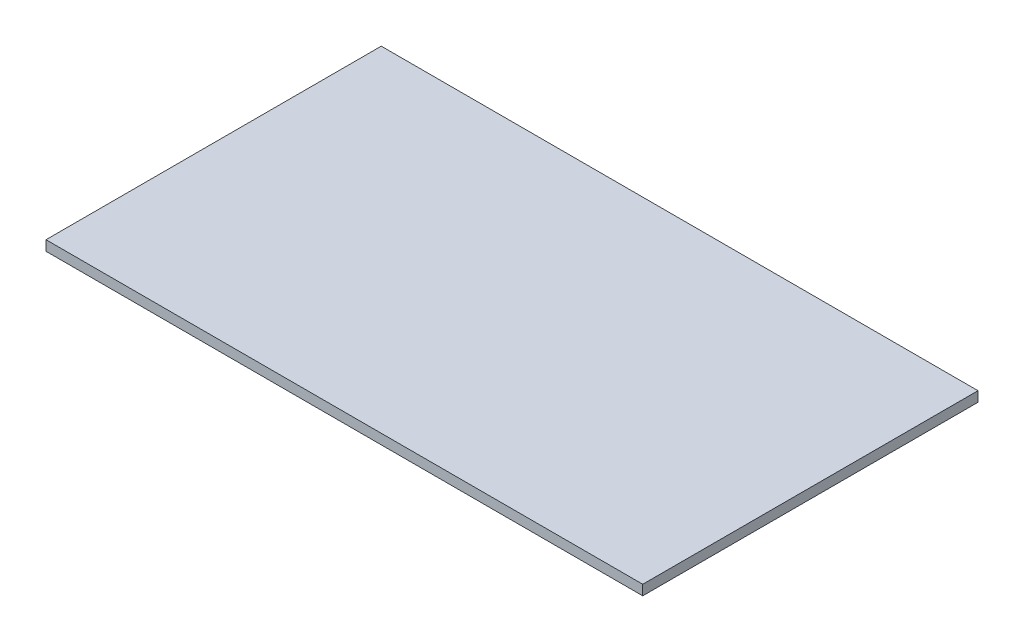
SolidWorks part; units mm, degrees
ref_plane "Front Plane" through (0, 0, 0) normal (0, 0, 1) x (1, 0, 0)
ref_plane "Top Plane" through (0, 0, 0) normal (0, 1, 0) x (1, 0, 0)
ref_plane "Right Plane" through (0, 0, 0) normal (1, 0, 0) x (0, 0, -1)
sketch "Sketch1" plane through (0, 0, 0) normal (0, 1, 0) x (1, 0, 0)
  line L1 (0, 0) -> (890, 0)
  line L2 (0, 0) -> (0, 500)
  line L3 (0, 500) -> (890, 500)
  line L4 (890, 0) -> (890, 500)
  dimension "D1" = 890
  dimension "D2" = 500
extrude "Boss-Extrude1" add sketch "Sketch1" along normal blind 15
